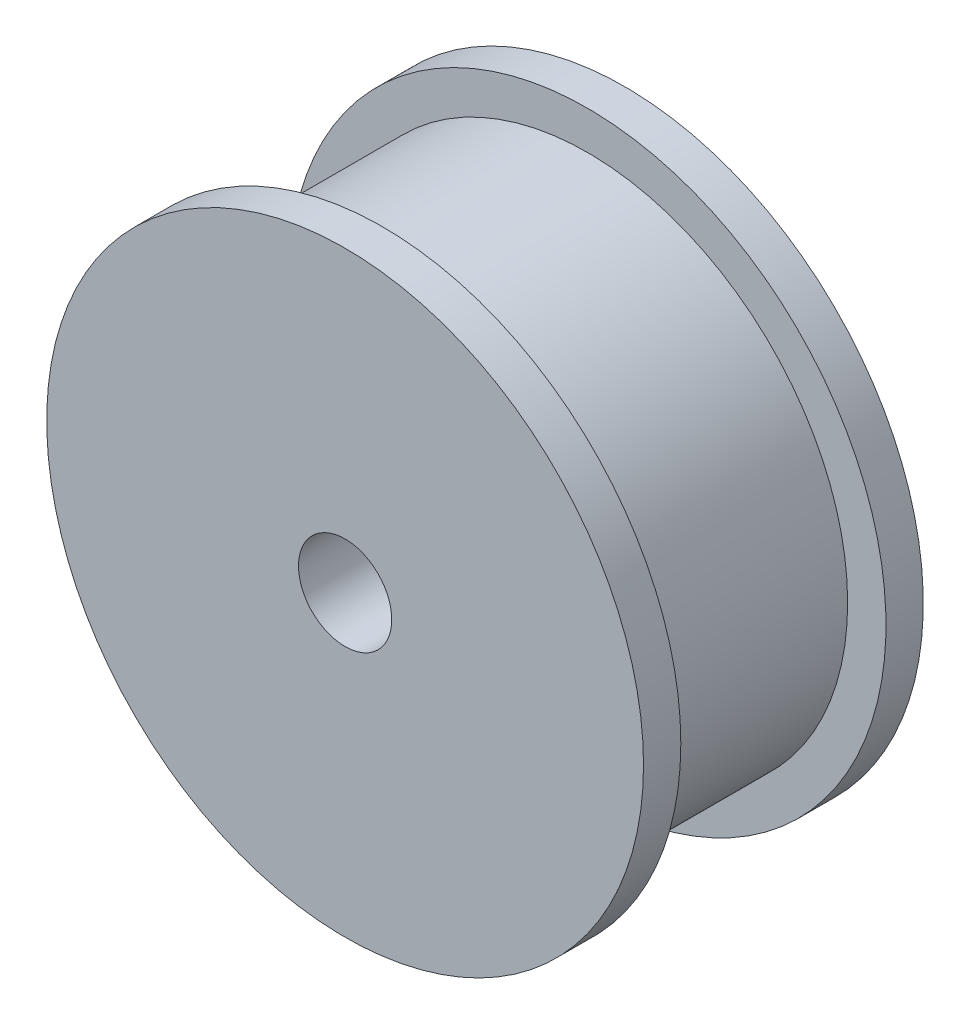
SolidWorks part; units mm, degrees
ref_plane "前视基准面" through (0, 0, 0) normal (0, 0, 1) x (1, 0, 0)
ref_plane "上视基准面" through (0, 0, 0) normal (0, 1, 0) x (1, 0, 0)
ref_plane "右视基准面" through (0, 0, 0) normal (1, 0, 0) x (0, 0, -1)
other "Configuration Table"
sketch "草图1" plane through (0, 0, 0) normal (0, 0, 1) x (1, 0, 0)
  circle A0 centre (0, 0) radius 13.945
  dimension "D1" = 27.89
extrude "凸台-拉伸1" add sketch "草图1" along normal mid plane 11
sketch "草图2" plane through (0, 0, 5.5) normal (0, 0, 1) x (1, 0, 0)
  circle A0 centre (0, 0) radius 16
  dimension "D1" = 32
extrude "凸台-拉伸2" add sketch "草图2" along normal blind 2
sketch "草图3" plane through (0, 0, -5.5) normal (0, 0, -1) x (-1, 0, 0)
  circle A0 centre (0, 0) radius 16
  dimension "D1" = 32
extrude "凸台-拉伸3" add sketch "草图3" along normal blind 2
sketch "草图4" plane through (0, 0, -7.5) normal (0, 0, -1) x (-1, 0, 0)
  circle A0 centre (0, 0) radius 2.5
  dimension "D1" = 5
extrude "切除-拉伸1" cut sketch "草图4" against normal through all both and the other way through all
